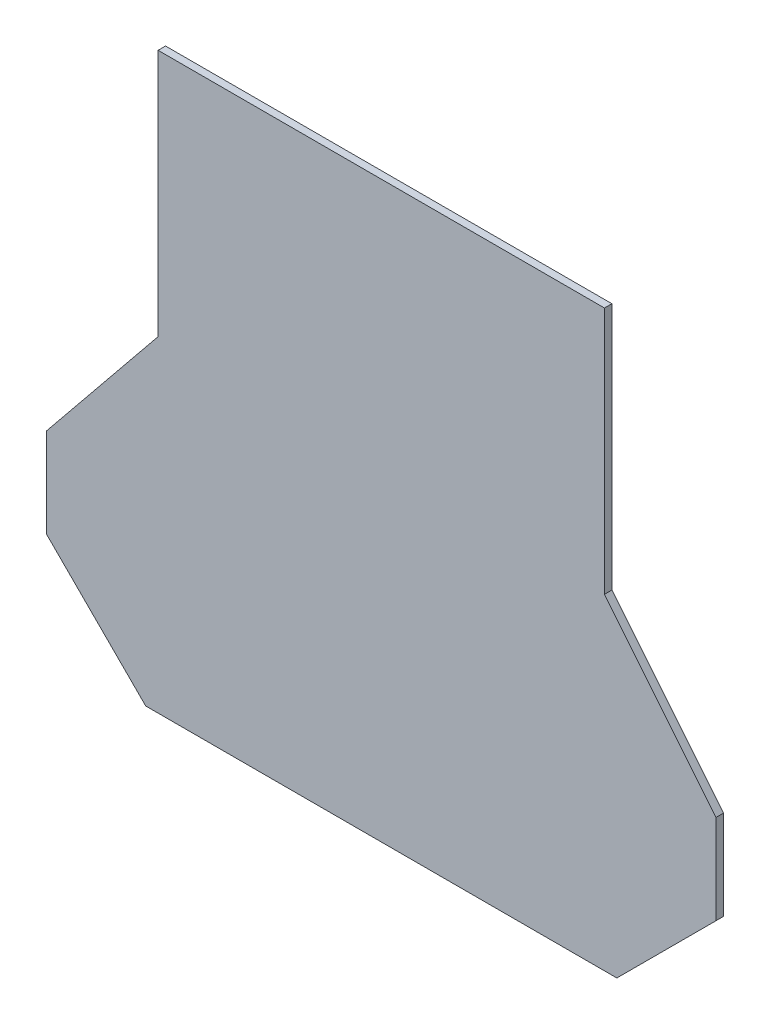
SolidWorks part; units mm, degrees
ref_plane "Plan de face" through (0, 0, 0) normal (0, 0, 1) x (1, 0, 0)
ref_plane "Plan de dessus" through (0, 0, 0) normal (0, 1, 0) x (1, 0, 0)
ref_plane "Plan de droite" through (0, 0, 0) normal (1, 0, 0) x (0, 0, -1)
sketch "Esquisse1" plane through (0, 0, 0) normal (0, 0, 1) x (1, 0, 0)
  line L3 (115.8733, 190.1528) -> (115.8733, 90.1528)
  line L4 (115.8733, 90.1528) -> (160.8733, 34.731)
  line L15 (160.8733, 34.731) -> (160.8733, -41.3472)
  line L16 (-64.1267, 190.1528) -> (115.8733, 190.1528)
  line L18 (-64.1267, 190.1528) -> (-64.1267, -41.8472) construction
  line L19 (-64.1267, 190.1528) -> (-64.1267, 90.1528)
  line L20 (115.8733, -41.8472) -> (115.8733, 190.1528) construction
  line L22 (160.8733, -1.8472) -> (160.8733, 193.1528) construction
  line L23 (-14.1267, 190.1528) -> (-64.1267, 190.1528) construction
  line L25 (-64.1267, 90.1528) -> (-109.1267, 34.731)
  line L26 (-109.1267, 193.1528) -> (-109.1267, -1.8472) construction
  line L27 (-109.1267, 34.731) -> (-109.1267, -41.3472)
  line L28 (-109.1267, -41.3472) -> (160.8733, -41.3472)
  point P0 (0, 32.2436)
  dimension "D1" = 0
  dimension "D2" = 100
  dimension "D3" = 100
  dimension "D4" = 0
  dimension "D5" = 0
extrude "Boss.-Extru.1" add sketch "Esquisse1" along normal blind 3
chamfer "Chanfrein1" distance 40 angle 45 2 edges at (160.8733, -41.3472, 1.5) (-109.1267, -41.3472, 1.5)
